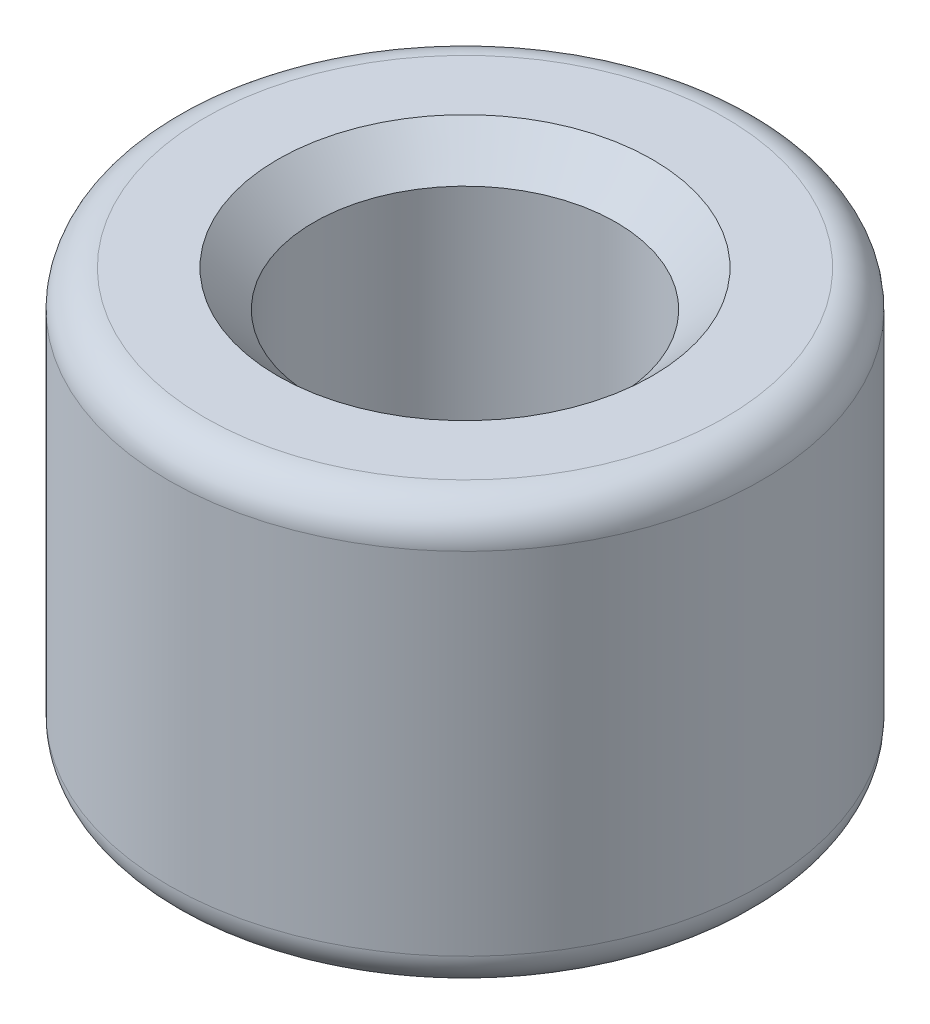
SolidWorks part; units mm, degrees
ref_plane "Front Plane" through (0, 0, 0) normal (0, 0, 1) x (1, 0, 0)
ref_plane "Top Plane" through (0, 0, 0) normal (0, 1, 0) x (1, 0, 0)
ref_plane "Right Plane" through (0, 0, 0) normal (1, 0, 0) x (0, 0, -1)
sketch "Sketch1" plane through (0, 0, 0) normal (0, 1, 0) x (1, 0, 0)
  circle A0 centre (0, 0) radius 1.25
  circle A1 centre (0, 0) radius 2.45
  dimension "D1" = 2.5
  dimension "D2" = 1.2
extrude "Boss-Extrude1" add sketch "Sketch1" along normal mid plane 3.5
chamfer "Chamfer1" distance 0.3 angle 45 2 edges at (0, -1.75, 1.25) (0, 1.75, 1.25)
fillet "Fillet1" radius 0.3 2 edges at (0, -1.75, 2.45) (0, 1.75, 2.45)
